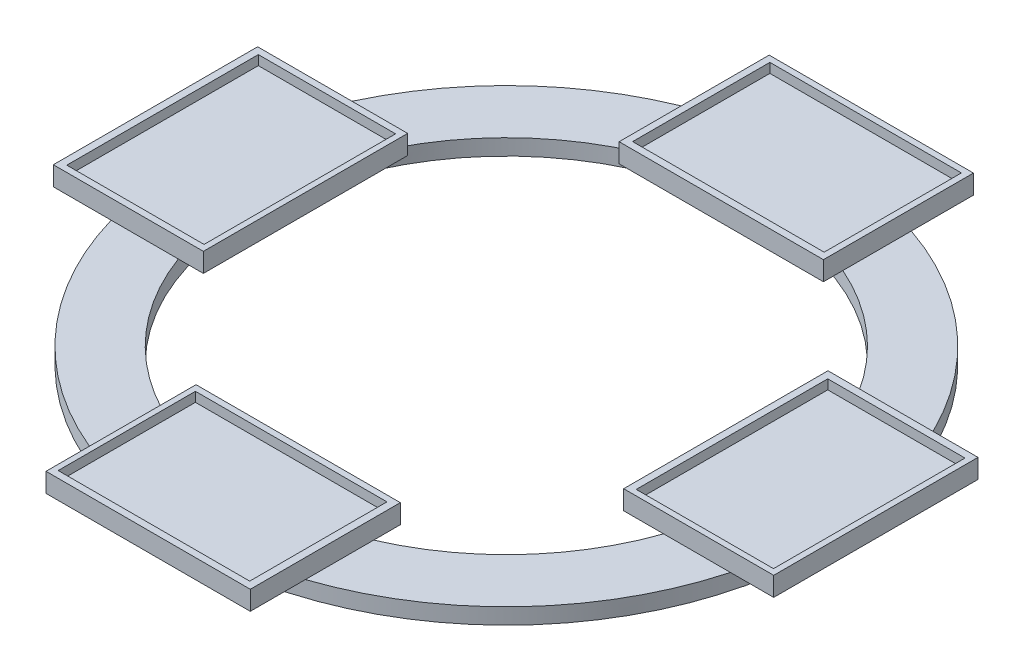
SolidWorks part; units mm, degrees
ref_plane "前视基准面" through (0, 0, 0) normal (0, 0, 1) x (1, 0, 0)
ref_plane "上视基准面" through (0, 0, 0) normal (0, 1, 0) x (1, 0, 0)
ref_plane "右视基准面" through (0, 0, 0) normal (1, 0, 0) x (0, 0, -1)
sketch "草图1" plane through (0, 0, 0) normal (0, 1, 0) x (1, 0, 0)
  circle A1 centre (0, 0) radius 100
  dimension "D1" = 200
extrude "凸台-拉伸2" add sketch "草图1" along normal blind 5 contours A1
sketch "草图3" plane through (0, 5, 0) normal (0, 1, 0) x (1, 0, 0)
  circle A0 centre (0, 0) radius 80
  dimension "D1" = 160
extrude "切除-拉伸1" cut sketch "草图3" against normal blind 5
sketch "草图4" plane through (0, 5, 0) normal (0, 1, 0) x (1, 0, 0)
  line L0 (-32.1629, -65.05) -> (31.8371, -65.05)
  line L1 (-31.8083, 114.1413) -> (32.1917, 114.1413)
  line L2 (-31.8083, 114.1413) -> (-31.8083, 67.1413)
  line L3 (-31.8083, 67.1413) -> (32.1917, 67.1413)
  line L4 (32.1917, 114.1413) -> (32.1917, 67.1413)
  line L5 (-32.1629, -65.05) -> (-32.1629, -112.05)
  line L6 (-32.1629, -112.05) -> (31.8371, -112.05)
  line L7 (31.8371, -65.05) -> (31.8371, -112.05)
  line L12 (-114.1907, 36.2753) -> (-67.1907, 36.2753)
  line L13 (-114.1907, 36.2753) -> (-114.1907, -27.7247)
  line L14 (-114.1907, -27.7247) -> (-67.1907, -27.7247)
  line L15 (-67.1907, 36.2753) -> (-67.1907, -27.7247)
  line L20 (63.0401, 37.7155) -> (110.0401, 37.7155)
  line L21 (63.0401, 37.7155) -> (63.0401, -26.2845)
  line L22 (63.0401, -26.2845) -> (110.0401, -26.2845)
  line L23 (110.0401, 37.7155) -> (110.0401, -26.2845)
  dimension "D1" = 64
  dimension "D2" = 47
  dimension "D3" = 47
  dimension "D4" = 64
  dimension "D5" = 64
  dimension "D6" = 47
extrude "凸台-拉伸4" add sketch "草图4" along normal blind 6
sketch "草图7" plane through (0, 11, 0) normal (0, 1, 0) x (1, 0, 0)
  line L0 (-30.4611, -66.9391) -> (29.5389, -66.9391)
  line L1 (-29.7253, 112.2828) -> (30.2747, 112.2828)
  line L2 (-29.7253, 112.2828) -> (-29.7253, 69.2828)
  line L3 (-29.7253, 69.2828) -> (30.2747, 69.2828)
  line L4 (30.2747, 112.2828) -> (30.2747, 69.2828)
  line L5 (-30.4611, -66.9391) -> (-30.4611, -109.9391)
  line L6 (-30.4611, -109.9391) -> (29.5389, -109.9391)
  line L7 (29.5389, -66.9391) -> (29.5389, -109.9391)
  line L8 (65.1974, 35.4908) -> (108.1974, 35.4908)
  line L9 (-111.9608, 34.2609) -> (-68.9608, 34.2609)
  line L10 (-111.9608, 34.2609) -> (-111.9608, -25.7391)
  line L11 (-111.9608, -25.7391) -> (-68.9608, -25.7391)
  line L12 (-68.9608, 34.2609) -> (-68.9608, -25.7391)
  line L13 (65.1974, 35.4908) -> (65.1974, -24.5092)
  line L14 (65.1974, -24.5092) -> (108.1974, -24.5092)
  line L15 (108.1974, 35.4908) -> (108.1974, -24.5092)
  dimension "D1" = 43
  dimension "D2" = 60
  dimension "D3" = 60
  dimension "D4" = 43
extrude "切除-拉伸2" cut sketch "草图7" against normal blind 3
